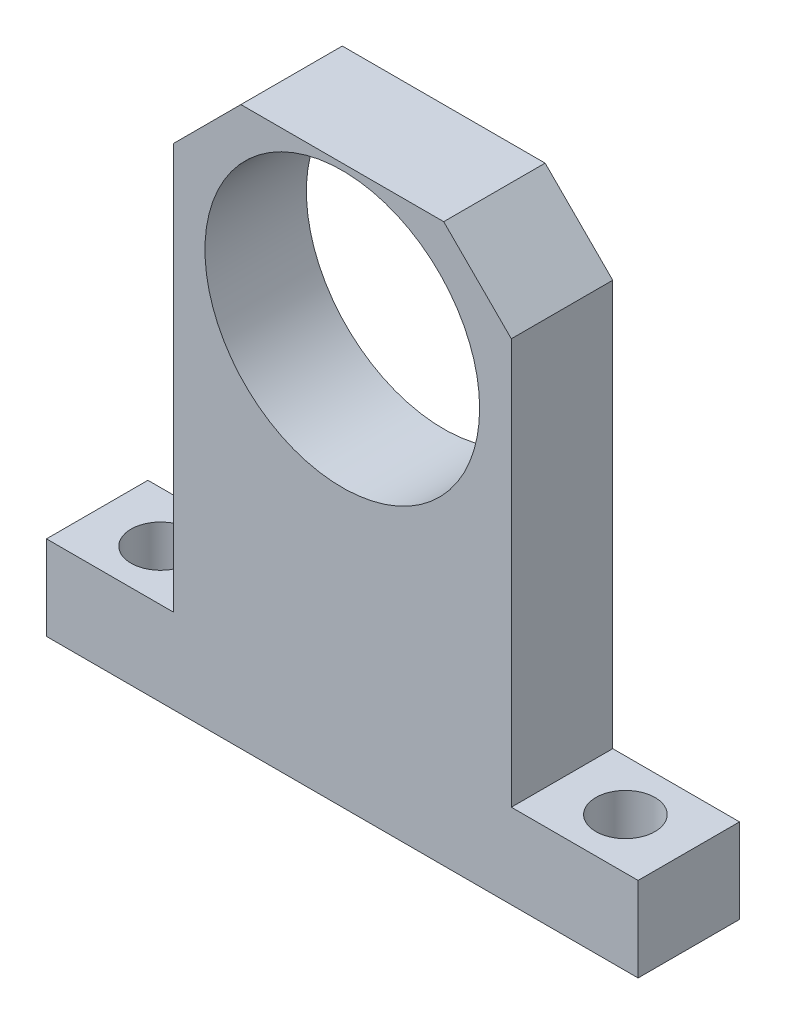
SolidWorks part; units mm, degrees
ref_plane "前基準面" through (0, 0, 0) normal (0, 0, 1) x (1, 0, 0)
ref_plane "上基準面" through (0, 0, 0) normal (0, 1, 0) x (1, 0, 0)
ref_plane "右基準面" through (0, 0, 0) normal (1, 0, 0) x (0, 0, -1)
sketch "草圖1" plane through (0, 0, 0) normal (0, 0, 1) x (1, 0, 0)
  line L0 (40, 0) -> (55, 0)
  line L2 (0, 0) -> (0, 56)
  line L3 (0, 56) -> (40, 56)
  line L4 (40, 0) -> (40, 56)
  line L5 (-15, 0) -> (0, 0)
  line L6 (-15, 0) -> (-15, -10)
  line L7 (-15, -10) -> (55, -10)
  line L8 (55, 0) -> (55, -10)
  circle A0 centre (20, 39) radius 16.25
  point P11 (20, 56)
  point P12 (20, -10)
  dimension "D1" = 32.5
  dimension "D2" = 49
  dimension "D3" = 10
  dimension "D4" = 17
  dimension "D5" = 40
  dimension "D6" = 15
extrude "填料-伸長1" add sketch "草圖1" along normal blind 12 contours A0 | L2 L3 L4 L0 L8 L7 L6 L5
sketch "草圖2" plane through (0, 0, 0) normal (0, 1, 0) x (1, 0, 0)
  line L0 (40, -12) -> (55, -12) construction
  line L1 (55, -12) -> (55, 0) construction
  circle A0 centre (47.5, -6) radius 3.5
  point P5 (47.5, -12)
  point P9 (55, -6)
  dimension "D1" = 7
extrude "除料-伸長2" cut sketch "草圖2" against normal through all contours A0
sketch "草圖3" plane through (0, 0, 0) normal (0, 1, 0) x (1, 0, 0)
  line L0 (-15, -12) -> (-15, 0) construction
  line L1 (-15, 0) -> (0, 0) construction
  circle A0 centre (-7.5, -6) radius 3.5
  point P5 (-15, -6)
  point P8 (-7.5, 0)
  dimension "D1" = 7
extrude "除料-伸長3" cut sketch "草圖3" against normal through all
chamfer "導角1" distance 8 angle 45 1 edges at (0, 56, 6)
chamfer "導角2" distance 8 angle 45 1 edges at (40, 56, 6)
